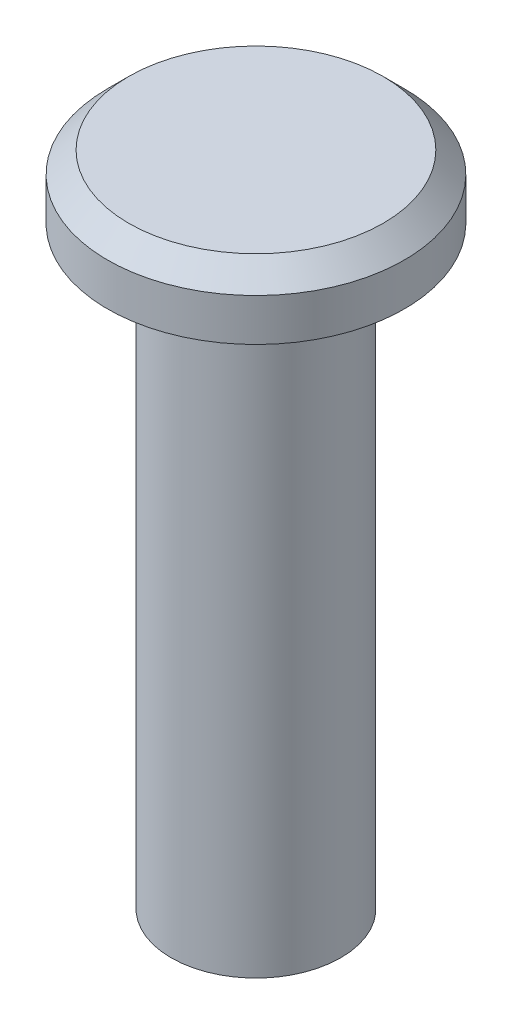
SolidWorks part; units mm, degrees
ref_plane "Front Plane" through (0, 0, 0) normal (0, 0, 1) x (1, 0, 0)
ref_plane "Top Plane" through (0, 0, 0) normal (0, 1, 0) x (1, 0, 0)
ref_plane "Right Plane" through (0, 0, 0) normal (1, 0, 0) x (0, 0, -1)
sketch "Sketch1" plane through (0, 0, 0) normal (0, 0, 1) x (1, 0, 0)
  line L0 (0, 0) -> (4, 0)
  line L1 (4, 0) -> (4, 28)
  line L2 (4, 28) -> (7, 28)
  line L3 (7, 28) -> (7, 30)
  line L4 (6, 31) -> (0, 31)
  line L5 (0, 31) -> (0, 0)
  line L6 (0, 33.605) -> (0, -11.1185) construction
  line L7 (7, 30) -> (6, 31)
  point P6 (7, 31)
  dimension "D1" = 8
  dimension "D2" = 28
  dimension "D3" = 3
  dimension "D4" = 14
revolve "Revolve1" add sketch "Sketch1" angle 360 about L6
